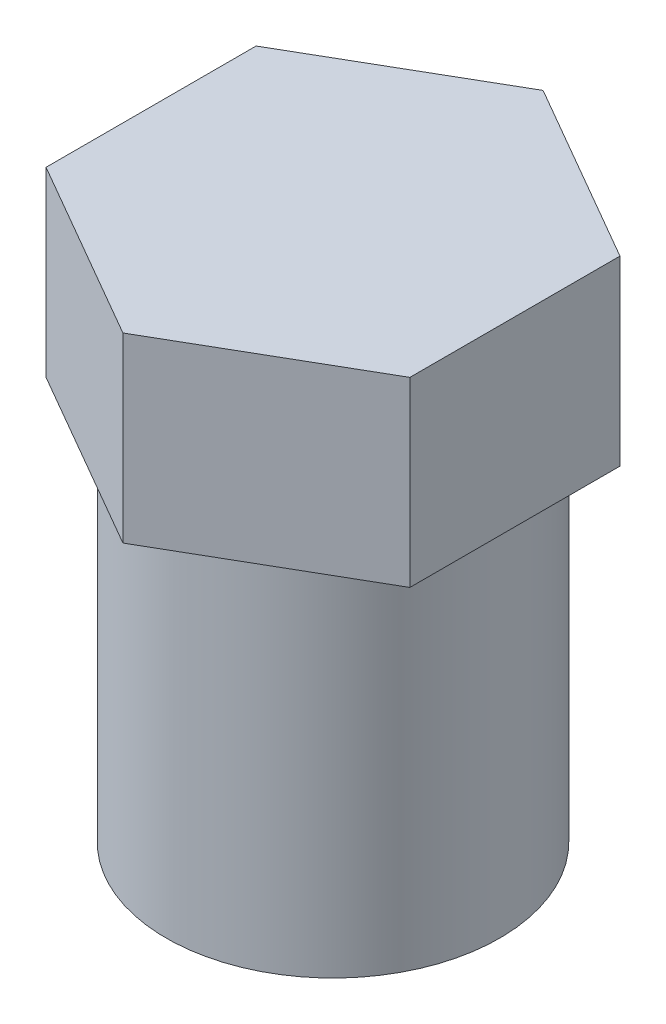
SolidWorks part; units mm, degrees
ref_plane "前视基准面" through (0, 0, 0) normal (0, 0, 1) x (1, 0, 0)
ref_plane "上视基准面" through (0, 0, 0) normal (0, 1, 0) x (1, 0, 0)
ref_plane "右视基准面" through (0, 0, 0) normal (1, 0, 0) x (0, 0, -1)
other "Configuration Table"
sketch "草图1" plane through (0, 0, 0) normal (0, 1, 0) x (1, 0, 0)
  line L0 (0, 6.9282) -> (0, 0) construction
  line L1 (0, 6.9282) -> (-6, 3.4641)
  line L2 (-6, 3.4641) -> (-6, -3.4641)
  line L3 (-6, -3.4641) -> (0, -6.9282)
  line L4 (0, -6.9282) -> (6, -3.4641)
  line L5 (6, -3.4641) -> (6, 3.4641)
  line L6 (6, 3.4641) -> (0, 6.9282)
  circle A0 centre (0, 0) radius 6 construction
  dimension "D1" = 12
extrude "凸台-拉伸1" add sketch "草图1" along normal blind 6
sketch "草图2" plane through (0, 0, 0) normal (0, -1, 0) x (1, 0, 0)
  circle A0 centre (0, 0) radius 5.5
  dimension "D1" = 11
extrude "凸台-拉伸2" add sketch "草图2" along normal blind 12
sketch "草图3" plane through (0, 0, 0) normal (1, 0, 0) x (0, 0, -1)
  line L0 (-3.4641, 0) -> (3.4641, 0) construction
  line L1 (0, -7) -> (0, 0) construction
  circle A0 centre (0, -7) radius 2
  dimension "D2" = 4
  dimension "D1" = 7
extrude "切除-拉伸1" cut sketch "草图3" against normal blind 12
sketch "草图4" plane through (0, -12, 0) normal (0, -1, 0) x (1, 0, 0)
  circle A0 centre (0, 0) radius 3
  dimension "D1" = 6
extrude "切除-拉伸2" cut sketch "草图4" against normal blind 12
